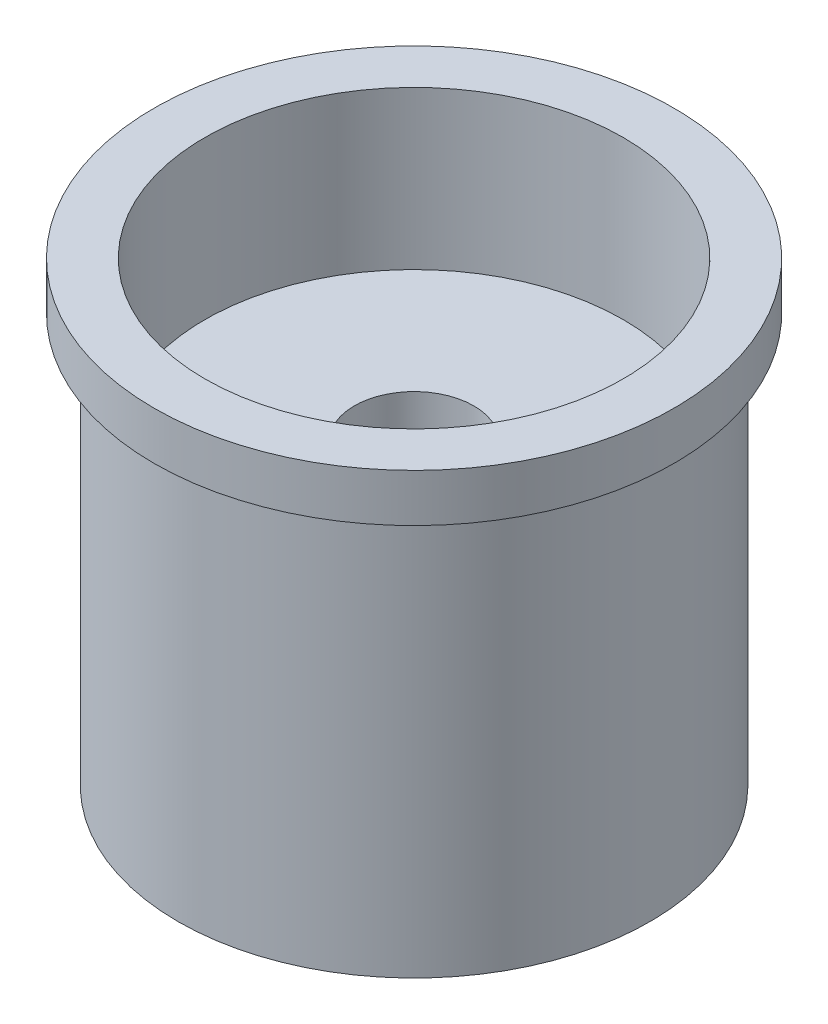
SolidWorks part; units mm, degrees
ref_plane "前视基准面" through (0, 0, 0) normal (0, 0, 1) x (1, 0, 0)
ref_plane "上视基准面" through (0, 0, 0) normal (0, 1, 0) x (1, 0, 0)
ref_plane "右视基准面" through (0, 0, 0) normal (1, 0, 0) x (0, 0, -1)
other "Configuration Table"
sketch "草图1" plane through (0, 0, 0) normal (0, 1, 0) x (1, 0, 0)
  circle A0 centre (0, 0) radius 19.75
  dimension "D1" = 39.5
extrude "凸台-拉伸1" add sketch "草图1" along normal blind 34.2
sketch "草图2" plane through (0, 34.2, 0) normal (0, 1, 0) x (1, 0, 0)
  circle A0 centre (0, 0) radius 21.75
  circle A1 centre (0, 0) radius 19.75 construction
  dimension "D1" = 2
extrude "凸台-拉伸2" add sketch "草图2" along normal blind 4
sketch "草图3" plane through (0, 0, 0) normal (0, -1, 0) x (1, 0, 0)
  circle A0 centre (0, 0) radius 5
  dimension "D1" = 10
extrude "切除-拉伸1" cut sketch "草图3" against normal blind 25
sketch "草图4" plane through (0, 38.2, 0) normal (0, 1, 0) x (1, 0, 0)
  circle A0 centre (0, 0) radius 17.5
  dimension "D1" = 35
extrude "切除-拉伸3" cut sketch "草图4" against normal up to surface (13.2 mm away) up to face at (0, 25, -5)
